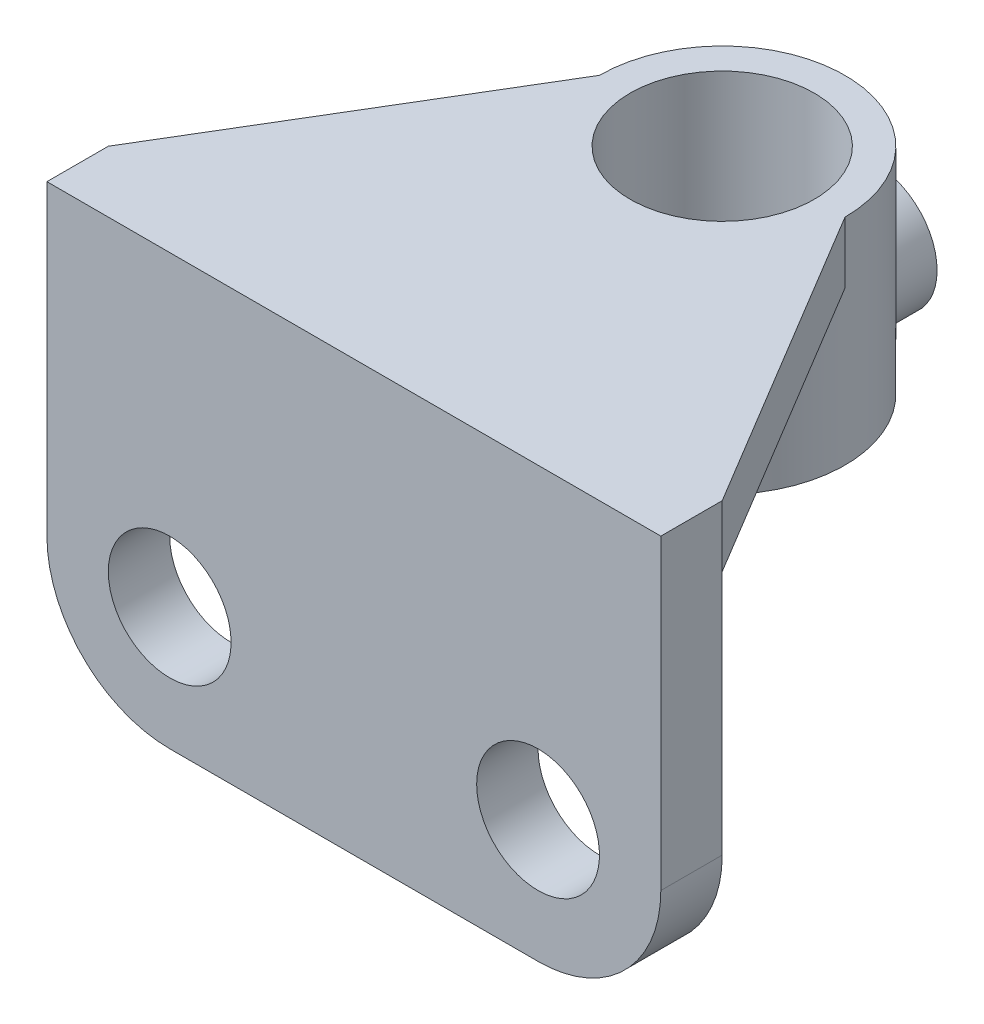
SolidWorks part; units mm, degrees
ref_plane "前基準面" through (0, 0, 0) normal (0, 0, 1) x (1, 0, 0)
ref_plane "上基準面" through (0, 0, 0) normal (0, 1, 0) x (1, 0, 0)
ref_plane "右基準面" through (0, 0, 0) normal (1, 0, 0) x (0, 0, -1)
sketch "草圖1" plane through (0, 0, 0) normal (0, 0, 1) x (1, 0, 0)
  line L0 (0, 45.4225) -> (0, -70.5986) construction
  line L1 (50, 35) -> (-50, 35)
  line L2 (50, 35) -> (50, -15)
  line L3 (30, -35) -> (-30, -35)
  line L4 (-50, 35) -> (-50, -15)
  line L5 (76.4085, 0) -> (-80.8099, 0) construction
  arc A0 (-30, -35) -> (-50, -15) centre (-30, -15) cw
  arc A1 (50, -15) -> (30, -35) centre (30, -15) cw
  point P12 (-50, -35)
  point P15 (50, -35)
  dimension "D3" = 20
  dimension "D1" = 100
  dimension "D2" = 70
extrude "填料-伸長1" add sketch "草圖1" against normal blind 10
sketch "草圖2" plane through (0, 0, -10) normal (0, 0, -1) x (-1, 0, 0)
  circle A0 centre (-30, -15) radius 10
  circle A1 centre (30, -15) radius 10
  dimension "D1" = 20
  dimension "D2" = 20
  dimension "D3" = 60
extrude "除料-伸長1" cut sketch "草圖2" against normal through all
sketch "草圖3" plane through (0, 35, 0) normal (0, 1, 0) x (1, 0, 0)
  line L0 (50, 0) -> (-50, 0) construction
  circle A0 centre (0, 60) radius 15
  circle A1 centre (0, 60) radius 20
  dimension "D1" = 30
  dimension "D2" = 40
  dimension "D3" = 60
extrude "填料-伸長2" add sketch "草圖3" against normal blind 35 separate body
sketch "草圖4" plane through (0, 35, 0) normal (0, 1, 0) x (1, 0, 0)
  line L0 (-50, 10) -> (-20, 60)
  line L1 (50, 10) -> (20, 60)
  line L2 (0, 60) -> (38.2271, 60) construction
  line L3 (-50, 10) -> (50, 10)
  circle A0 centre (0, 60) radius 20 construction
  arc A1 (-20, 60) -> (20, 60) centre (0, 60) ccw
  circle A3 centre (0, 60) radius 20
  circle A4 centre (0, 60) radius 20
  circle M4 centre (0, 60) radius 20
  dimension "D1" = 0
extrude "填料-伸長3" add sketch "草圖4" against normal blind 10 contours L0 L3 L1 M4
sketch "草圖6" plane through (0, -35, 0) normal (0, -1, 0) x (1, 0, 0)
  line L0 (-30, -10) -> (30, -10) construction
  line L1 (5, -10) -> (-5, -10)
  line L2 (5, -10) -> (5, -40.6351)
  line L4 (-5, -10) -> (-5, -40.6351)
  line L5 (0, -28.9576) -> (0, 21.7585) construction
  circle A1 centre (0, -60) radius 20
  circle A2 centre (0, -60) radius 20
  line M8 (-30, -10) -> (30, -10)
  dimension "D1" = 10
  dimension "D2" = 0
extrude "填料-伸長4" add sketch "草圖6" against normal up to surface (60 mm away) contours L5 A2 L2 L1 | A2 L5 L4 M8
sketch "草圖7" plane through (-5, 0, 0) normal (-1, 0, 0) x (0, 0, 1)
  line L0 (-10, -35) -> (-40.6351, 0)
  line L1 (-40.6351, 0) -> (-40.6351, -35)
  line L2 (-40.6351, -35) -> (-10, -35)
extrude "除料-伸長3" cut sketch "草圖7" against normal blind 10 contours L1 L2 L0
ref_plane "平面1" through (0, 0, -85) normal (0, 0, 1) x (1, 0, 0)
sketch "草圖8" plane through (0, 0, -85) normal (0, 0, 1) x (1, 0, 0)
  line L1 (-20, 0) -> (20, 0) construction
  line L2 (-20, 0) -> (20, 0)
  line L3 (0, 8.1353) -> (0, -24.2527) construction
  circle A0 centre (0, 10) radius 10
  circle A1 centre (0, 10) radius 7
  point P6 (0, 0)
  point P9 (0, 0)
  dimension "D1" = 20
  dimension "D2" = 14
  dimension "D3" = 10
extrude "填料-伸長5" add sketch "草圖8" along normal blind 10 contours L3 A0 A1 | A0 L3 A1
